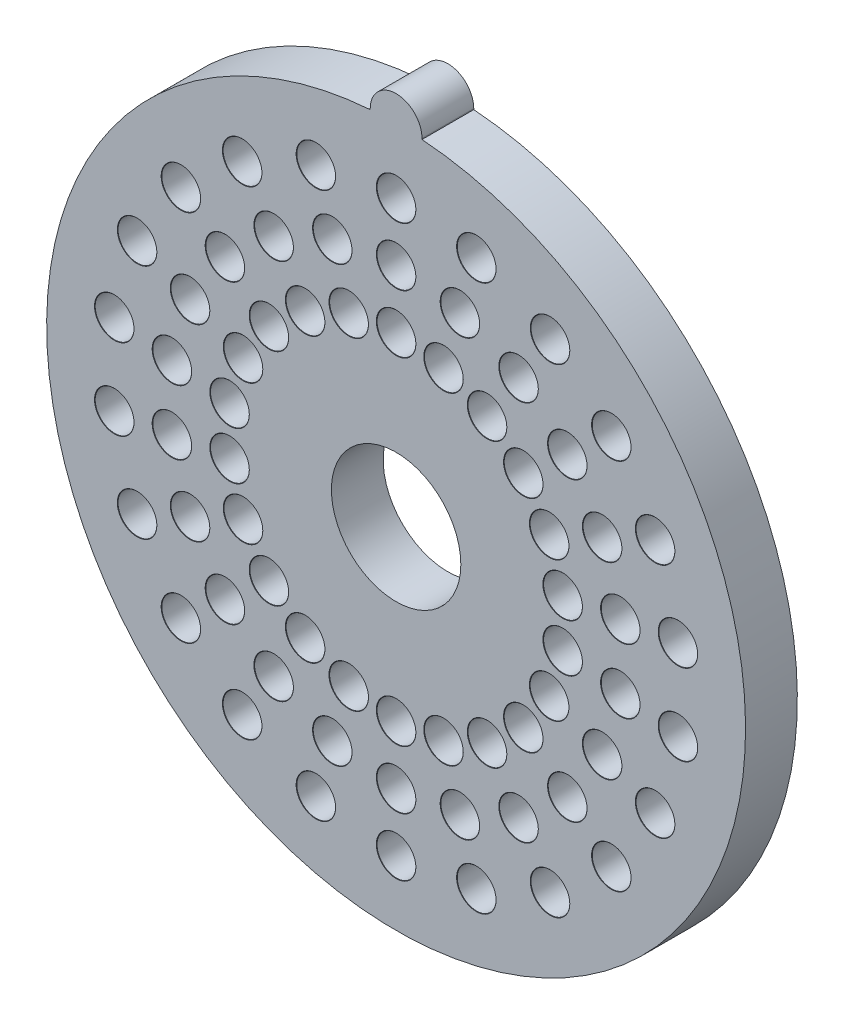
SolidWorks part; units mm, degrees
ref_plane "Front Plane" through (0, 0, 0) normal (0, 0, 1) x (1, 0, 0)
ref_plane "Top Plane" through (0, 0, 0) normal (0, 1, 0) x (1, 0, 0)
ref_plane "Right Plane" through (0, 0, 0) normal (1, 0, 0) x (0, 0, -1)
sketch "Sketch1" plane through (0, 0, 0) normal (0, 0, 1) x (1, 0, 0)
  line L0 (0, 27) -> (0, 0) construction
  line L1 (-2, 26.9258) -> (-2, 27)
  line L2 (2, 26.9258) -> (2, 27)
  arc A0 (-2, 26.9258) -> (2, 26.9258) centre (0, 0) ccw
  arc A2 (2, 27) -> (-2, 27) centre (0, 27) ccw
  point P5 (0, 27)
  dimension "D1" = 27
  dimension "D2" = 2
extrude "Boss-Extrude1" add sketch "Sketch1" along normal blind 4
hole_wizard "Ø3.0mm Dowel Hole1" positions "Sketch2" profile "Sketch3" hole size "Ø3.0" standard "ISO" end condition through all
sketch "Sketch2" plane through (0, 0, 4) normal (0, 0, 1) x (1, 0, 0)
  line L0 (0, 22) -> (0, 0)
  point P0 (0, 22)
  dimension "D1" = 22
sketch "Sketch3" plane through (0, 22, 4) normal (1, 0, 0) x (0, -1, 0)
  line L0 (0, 0) -> (0, 4)
  line L1 (0, 4) -> (1.5, 4)
  line L2 (1.5, 4) -> (1.5, 0.025)
  line L3 (1.5, 0.025) -> (1.525, 0)
  line L5 (1.525, 0) -> (0, 0)
  line L6 (-1.5, 0.025) -> (-1.525, 0) construction
  line L11 (0, -6.35) -> (0, 107.95) construction
  dimension "Thru Hole Dia." = 3
  dimension "Thru Hole Depth" = 4
  dimension "Near C'Sink Dia." = 3.05
  dimension "Near C'Sink Angle" = 90
pattern_linear "LPattern1" count 3 spacing 4.5 along (0, -1, 0) of "Ø3.0mm Dowel Hole1"
pattern_circular "CirPattern2" count 22 over 360 about axis through (0, 0, 0) along (0, 0, 1) of "LPattern1", "Ø3.0mm Dowel Hole1"
sketch "Sketch4" plane through (0, 0, 4) normal (0, 0, 1) x (1, 0, 0)
  circle A0 centre (0, 0) radius 5
  dimension "D1" = 10
extrude "Cut-Extrude1" cut sketch "Sketch4" against normal through all
